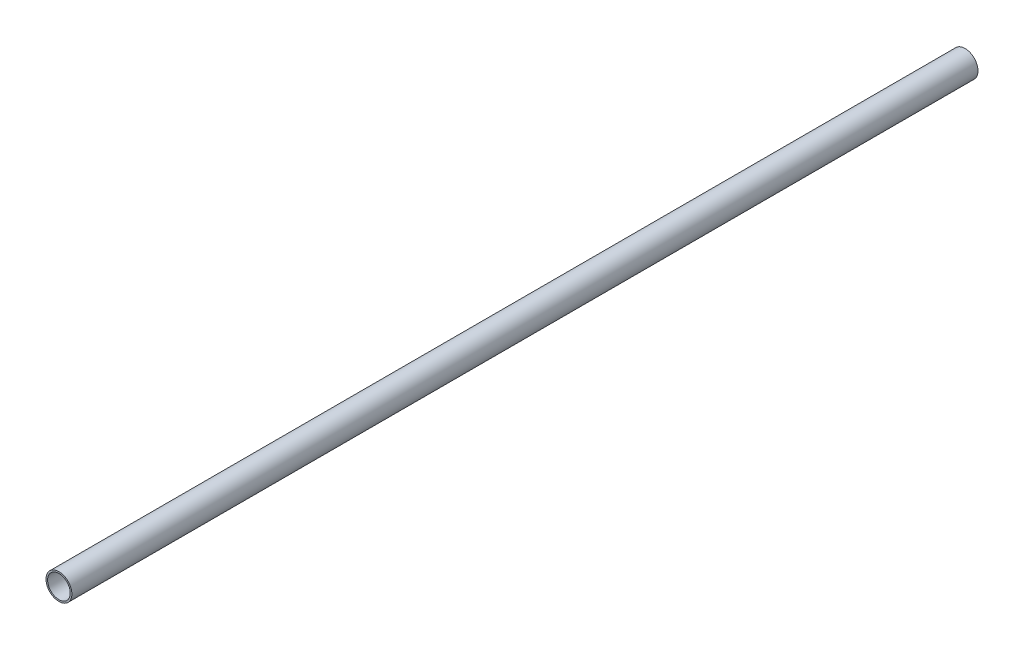
SolidWorks part; units mm, degrees
material "Poltrusion Carbon Fiber"
ref_plane "Front Plane" through (0, 0, 0) normal (0, 0, 1) x (1, 0, 0)
ref_plane "Top Plane" through (0, 0, 0) normal (0, 1, 0) x (1, 0, 0)
ref_plane "Right Plane" through (0, 0, 0) normal (1, 0, 0) x (0, 0, -1)
sketch "Эскиз1" plane through (0, 0, 0) normal (0, 0, 1) x (1, 0, 0)
  circle A0 centre (0, 0) radius 4
  circle A1 centre (0, 0) radius 3.5
  dimension "D1" = 8
  dimension "D2" = 0.5
extrude "Бобышка-Вытянуть1" add sketch "Эскиз1" along normal mid plane 280
